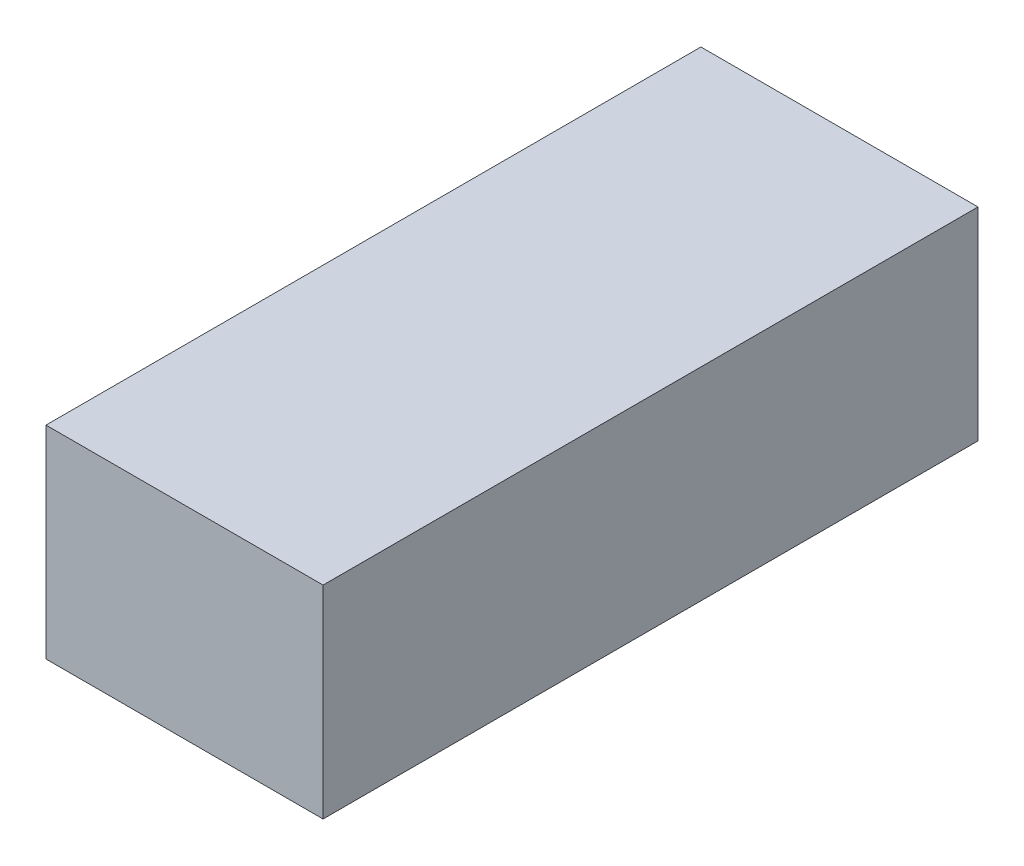
SolidWorks part; units mm, degrees
ref_plane "Front Plane" through (0, 0, 0) normal (0, 0, 1) x (1, 0, 0)
ref_plane "Top Plane" through (0, 0, 0) normal (0, 1, 0) x (1, 0, 0)
ref_plane "Right Plane" through (0, 0, 0) normal (1, 0, 0) x (0, 0, -1)
sketch "Sketch1" plane through (0, 0, 0) normal (0, 1, 0) x (1, 0, 0)
  line L0 (0, -55) -> (0, 55) construction
  line L1 (-34.925, 165.1) -> (34.925, 165.1)
  line L2 (-34.925, 165.1) -> (-34.925, 0)
  line L3 (-34.925, 0) -> (34.925, 0)
  line L4 (34.925, 165.1) -> (34.925, 0)
  line L5 (-55, 0) -> (55, 0) construction
  line L8 (0, 165.1) -> (0, 0) construction
  dimension "D1" = 69.85
  dimension "D2" = 165.1
extrude "Boss-Extrude1" add sketch "Sketch1" along normal blind 51.0794
